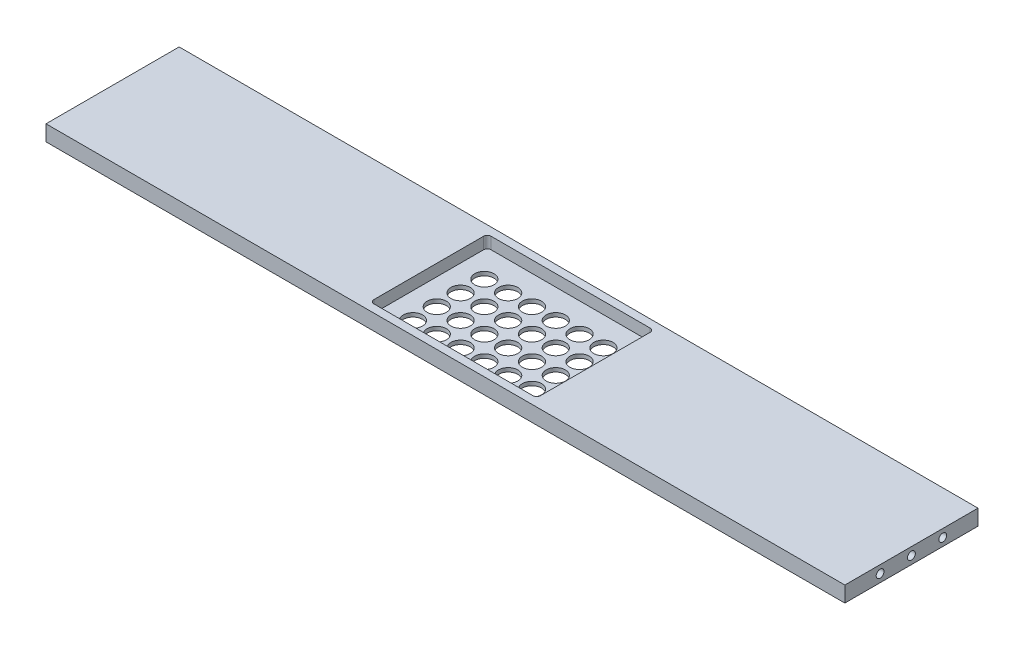
SolidWorks part; units mm, degrees
material "6061 Alloy"
ref_plane "Front" through (0, 0, 0) normal (0, 0, 1) x (1, 0, 0)
ref_plane "Top" through (0, 0, 0) normal (0, 1, 0) x (1, 0, 0)
ref_plane "Right" through (0, 0, 0) normal (1, 0, 0) x (0, 0, -1)
sketch "Sketch2" plane through (0, 0, 0) normal (0, 0, 1) x (1, 0, 0)
  line L5 (0, -12.7) -> (0, 0) construction
  line L9 (-323.85, -12.7) -> (-323.85, 0)
  line L11 (323.85, -12.7) -> (323.85, 0)
  line L15 (-323.85, -12.7) -> (323.85, -12.7)
  line L17 (-323.85, 0) -> (323.85, 0)
  dimension "D3" = 647.7
  dimension "D4" = 12.7
extrude "Boss-Extrude1" add sketch "Sketch2" along normal mid plane 107.95
sketch "Sketch3" plane through (0, 0, 0) normal (0, 1, 0) x (1, 0, 0)
  line L1 (64.5, 47.5) -> (-64.5, 47.5)
  line L2 (67.5, 44.5) -> (67.5, -44.5)
  line L3 (64.5, -47.5) -> (-64.5, -47.5)
  line L4 (-67.5, 44.5) -> (-67.5, -44.5)
  line L5 (67.5, 47.5) -> (-67.5, -47.5) construction
  line L6 (67.5, -47.5) -> (-67.5, 47.5) construction
  arc A0 (64.5, 47.5) -> (67.5, 44.5) centre (64.5, 44.5) cw
  arc A1 (-67.5, 44.5) -> (-64.5, 47.5) centre (-64.5, 44.5) cw
  arc A2 (-64.5, -47.5) -> (-67.5, -44.5) centre (-64.5, -44.5) cw
  arc A3 (67.5, -44.5) -> (64.5, -47.5) centre (64.5, -44.5) cw
  point P0 (0, 0)
  dimension "D3" = 3
  dimension "D1" = 135
  dimension "D2" = 95
extrude "Cut-Extrude1" cut sketch "Sketch3" against normal offset from surface (9.525 mm away) 3.175 up to face at (0, -12.7, 0)
sketch "Sketch4" plane through (0, -9.525, 0) normal (0, 1, 0) x (1, 0, 0)
  line L0 (-46.526, 24.116) -> (-46.526, 4.816) construction
  line L1 (64.5, -47.5) -> (-64.5, -47.5) construction
  line L2 (67.5, -44.5) -> (67.5, 44.5) construction
  circle A0 centre (-46.526, 24.116) radius 7.81
  circle A1 centre (-27.226, 24.116) radius 7.81
  circle A2 centre (-7.926, 24.116) radius 7.81
  circle A3 centre (11.374, 24.116) radius 7.81
  circle A4 centre (30.674, 24.116) radius 7.81
  circle A5 centre (49.974, 24.116) radius 7.81
  circle A6 centre (-27.226, 4.816) radius 7.81
  circle A7 centre (-7.926, 4.816) radius 7.81
  circle A8 centre (11.374, 4.816) radius 7.81
  circle A9 centre (30.674, 4.816) radius 7.81
  circle A10 centre (49.974, 4.816) radius 7.81
  circle A11 centre (-27.226, -14.484) radius 7.81
  circle A12 centre (-7.926, -14.484) radius 7.81
  circle A13 centre (11.374, -14.484) radius 7.81
  circle A14 centre (30.674, -14.484) radius 7.81
  circle A15 centre (49.974, -14.484) radius 7.81
  circle A16 centre (-27.226, -33.784) radius 7.81
  circle A17 centre (-7.926, -33.784) radius 7.81
  circle A18 centre (11.374, -33.784) radius 7.81
  circle A19 centre (30.674, -33.784) radius 7.81
  circle A20 centre (49.974, -33.784) radius 7.81
  circle A21 centre (-46.526, 4.816) radius 7.81
  circle A22 centre (-46.526, -14.484) radius 7.81
  circle A23 centre (-46.526, -33.784) radius 7.81
  dimension "D1" = 13.716
  dimension "D2" = 6
  dimension "D4" = 4
  dimension "D7" = 15.62
  dimension "D3" = 19.3
  dimension "D5" = 17.526
extrude "Cut-Extrude2" cut sketch "Sketch4" against normal through all both and the other way through all
hole_wizard "1/4\"-20 threaded hole" positions "Sketch7" profile "Sketch6" hole size "#97" standard "ANSI Inch"
sketch "Sketch7" plane through (-323.85, 0, 0) normal (-1, 0, 0) x (0, 0, 1)
  line L0 (-53.975, -6.35) -> (53.975, -6.35) construction
  line L1 (-53.975, 0) -> (-53.975, -12.7) construction
  line L2 (53.975, 0) -> (53.975, -12.7) construction
  point P0 (-25.4, -6.35)
  point P2 (0, -6.35)
  point P4 (25.4, -6.35)
  dimension "D1" = 25.4
  dimension "D2" = 25.4
sketch "Sketch6" plane through (-323.85, -6.35, -25.4) normal (0, 1, 0) x (0, 0, 1)
  line L0 (0, 0) -> (0, 52.7077)
  line L1 (0, 52.7077) -> (3.175, 50.8)
  line L2 (3.175, 50.8) -> (3.175, 0)
  line L5 (3.175, 0) -> (0, 0)
  line L10 (0, 52.7077) -> (-3.175, 50.8) construction
  line L11 (0, -6.35) -> (0, 107.95) construction
  dimension "Hole Dia." = 6.35
  dimension "Hole Depth" = 50.8
  dimension "Drill Angle" = 118
mirror "Mirror1" about plane through (0, 0, 0) normal (1, 0, 0) of "1/4\"-20 threaded hole"
